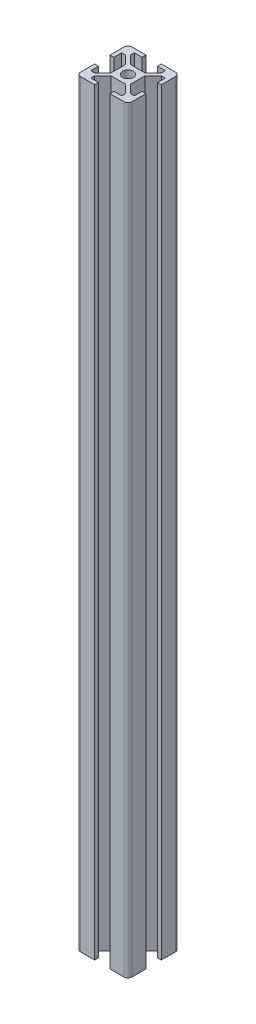
SolidWorks part; units mm, degrees
material "6063-T5"
ref_plane "Front Plane" through (0, 0, 0) normal (0, 0, 1) x (1, 0, 0)
ref_plane "Top Plane" through (0, 0, 0) normal (0, 1, 0) x (1, 0, 0)
ref_plane "Right Plane" through (0, 0, 0) normal (1, 0, 0) x (0, 0, -1)
sketch "Sketch1" plane through (0, 0, 0) normal (0, 1, 0) x (1, 0, 0)
  line L1 (-8.5, -10) -> (8.5, -10)
  line L2 (-10, -8.5) -> (-10, 8.5)
  line L3 (-8.5, 10) -> (8.5, 10)
  line L4 (10, -8.5) -> (10, 8.5)
  line L5 (-10, -10) -> (10, 10) construction
  line L6 (-10, 10) -> (10, -10) construction
  arc A0 (-8.5, -10) -> (-10, -8.5) centre (-8.5, -8.5) cw
  arc A1 (8.5, -10) -> (10, -8.5) centre (8.5, -8.5) ccw
  arc A2 (8.5, 10) -> (10, 8.5) centre (8.5, 8.5) cw
  arc A3 (-10, 8.5) -> (-8.5, 10) centre (-8.5, 8.5) cw
  point P0 (0, 0)
  dimension "D3" = 1.5
  dimension "D1" = 20
  dimension "D2" = 20
extrude "Boss-Extrude1" add sketch "Sketch1" along normal mid plane 295.275
sketch "Sketch2" plane through (0, 0, 0) normal (0, 1, 0) x (1, 0, 0)
  line L0 (-16.6017, 0) -> (16.6017, 0) construction
  line L1 (0, -12.6601) -> (0, 12.6601) construction
  line L2 (-6, 8.5) -> (6, 8.5) construction
  line L3 (-3, 10) -> (3, 10)
  line L4 (8.5, 10) -> (-8.5, 10) construction
  line L5 (-2.63, 3.8) -> (2.63, 3.8) construction
  line L6 (-3.655, -3.655) -> (3.655, -3.655) construction
  line L7 (-3.655, -3.655) -> (-3.655, 3.655) construction
  line L8 (-3.655, 3.655) -> (3.655, 3.655) construction
  line L9 (3.655, -3.655) -> (3.655, 3.655) construction
  line L10 (-3.655, -3.655) -> (3.655, 3.655) construction
  line L11 (-3.655, 3.655) -> (3.655, -3.655) construction
  line L12 (-9.5607, -9.5607) -> (9.5607, 9.5607) construction
  line L13 (-6, 7.0607) -> (-2.7393, 3.8)
  line L14 (-6, 8.5) -> (-6, 7.0607)
  line L15 (3, 10) -> (3, 8.5)
  line L16 (3, 8.5) -> (6, 8.5)
  line L17 (6, 8.5) -> (6, 7.0607)
  line L18 (6, 7.0607) -> (2.7393, 3.8)
  line L19 (2.7393, 3.8) -> (-2.7393, 3.8)
  line L20 (2.5943, 3.655) -> (6, 7.0607)
  line L21 (-3, 8.5) -> (-6, 8.5)
  line L22 (-3, 10) -> (-3, 8.5)
  line L23 (8.5, -3) -> (8.5, -6)
  line L24 (10, 3) -> (10, -3)
  line L25 (10, -3) -> (8.5, -3)
  line L26 (10, 3) -> (8.5, 3)
  line L27 (8.5, 3) -> (8.5, 6)
  line L28 (8.5, 6) -> (7.0607, 6)
  line L29 (7.0607, 6) -> (3.8, 2.7393)
  line L30 (3.8, -2.7393) -> (3.8, 2.7393)
  line L31 (7.0607, -6) -> (3.8, -2.7393)
  line L32 (8.5, -6) -> (7.0607, -6)
  line L33 (-3, -8.5) -> (-6, -8.5)
  line L34 (3, -10) -> (-3, -10)
  line L35 (-3, -10) -> (-3, -8.5)
  line L36 (3, -10) -> (3, -8.5)
  line L37 (3, -8.5) -> (6, -8.5)
  line L38 (6, -8.5) -> (6, -7.0607)
  line L39 (6, -7.0607) -> (2.7393, -3.8)
  line L40 (-2.7393, -3.8) -> (2.7393, -3.8)
  line L41 (-6, -7.0607) -> (-2.7393, -3.8)
  line L42 (-6, -8.5) -> (-6, -7.0607)
  line L43 (-8.5, 3) -> (-8.5, 6)
  line L44 (-10, -3) -> (-10, 3)
  line L45 (-10, 3) -> (-8.5, 3)
  line L46 (-10, -3) -> (-8.5, -3)
  line L47 (-8.5, -3) -> (-8.5, -6)
  line L48 (-8.5, -6) -> (-7.0607, -6)
  line L49 (-7.0607, -6) -> (-3.8, -2.7393)
  line L50 (-3.8, 2.7393) -> (-3.8, -2.7393)
  line L51 (-7.0607, 6) -> (-3.8, 2.7393)
  line L52 (-8.5, 6) -> (-7.0607, 6)
  circle A0 centre (0, 0) radius 2.1 construction
  arc A1 (10, 8.5) -> (8.5, 10) centre (8.5, 8.5) ccw construction
  point P6 (0, 0)
  point P9 (0, 0)
  point P12 (0, 8.5)
  point P17 (0, 10)
  point P21 (-9.0303, -10.091)
  point P24 (0, 3.8)
  point P30 (0, 0)
  point P31 (10.091, 9.0303)
  point P32 (-10.091, -9.0303)
  point P33 (9.0303, 10.091)
  point P41 (0, 3.8)
  point P75 (0, 0)
  dimension "D1" = 4.2
  dimension "D2" = 12
  dimension "D3" = 8.5
  dimension "D4" = 6
  dimension "D5" = 7.31
  dimension "D6" = 7.31
  dimension "D7" = 4.7
  dimension "D8" = 4
extrude "Cut-Extrude1" cut sketch "Sketch2" against normal through all and the other way through all contours L51 L50 L49 L48 L47 L46 L44 L45 L43 L52 | L29 L30 L31 L32 L23 L25 L24 L26 L27 L28 | L39 L40 L41 L42 L33 L35 L34 L36 L37 L38 | A0 | L17 L16 L15 L3 L22 L21 L14 L13 L19 L18
sketch "Sketch3" plane through (0, 147.6375, 0) normal (0, 1, 0) x (1, 0, 0)
  circle A0 centre (0, 0) radius 2.1
  dimension "D1" = 4.2
extrude "Cut-Extrude2" cut sketch "Sketch3" against normal blind 13
sketch "Sketch4" plane through (0, -147.6375, 0) normal (0, -1, 0) x (1, 0, 0)
  circle A0 centre (0, 0) radius 2.1
  dimension "D1" = 4.2
extrude "Cut-Extrude3" cut sketch "Sketch4" against normal blind 13
